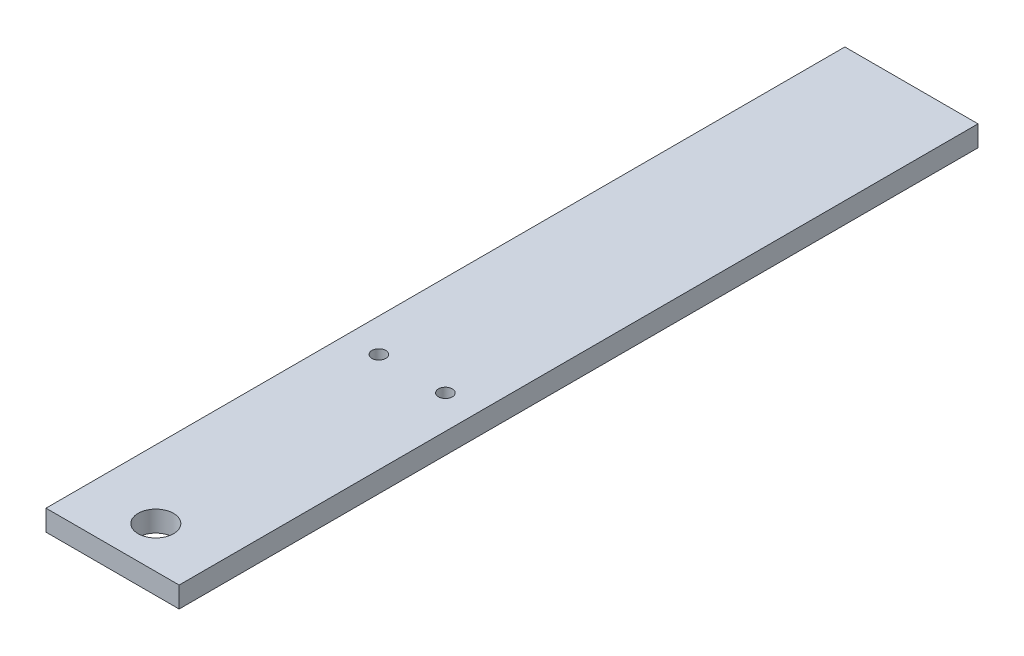
SolidWorks part; units mm, degrees
ref_plane "Front Plane" through (0, 0, 0) normal (0, 0, 1) x (1, 0, 0)
ref_plane "Top Plane" through (0, 0, 0) normal (0, 1, 0) x (1, 0, 0)
ref_plane "Right Plane" through (0, 0, 0) normal (1, 0, 0) x (0, 0, -1)
sketch "Sketch1" plane through (0, 0, 0) normal (0, 0, 1) x (1, 0, 0)
  line L0 (0, 3.9688) -> (0, -3.9688)
  line L1 (-25.4, 0) -> (25.4, 0) construction
  point P6 (0, 0)
  dimension "Width" = 50.8
  dimension "Thk" = 7.9375
sketch "Sketch2" plane through (0, 0, 0) normal (1, 0, 0) x (0, 0, -1)
  line L0 (76.2, 0) -> (-76.2, 0)
  point P4 (0, 0)
  dimension "Length" = 152.4
sketch "Sketch3" plane through (0, 0, 0) normal (0, 0, 1) x (1, 0, 0)
  line L1 (25.4, 3.9688) -> (-25.4, 3.9688)
  line L2 (25.4, 3.9688) -> (25.4, -3.9688)
  line L3 (25.4, -3.9688) -> (-25.4, -3.9688)
  line L4 (-25.4, 3.9688) -> (-25.4, -3.9688)
  line L5 (25.4, 3.9688) -> (-25.4, -3.9688) construction
  line L6 (25.4, -3.9688) -> (-25.4, 3.9688) construction
  point P0 (0, 0)
extrude "Boss-Extrude1" add sketch "Sketch3" along normal up to vertex (76.2 mm away) and the other way up to vertex (76.2 mm away) up to point (0, 0, 76.2) other way up to point (0, 0, -76.2)
sketch "Sketch4" plane through (0, 3.9688, 0) normal (0, 1, 0) x (1, 0, 0)
  point P0 (0.6258, -60.325)
hole_wizard "M12 Clearance Hole2" positions "Sketch5" profile "Sketch7" hole size "M12" standard "ANSI Metric" end condition through all
sketch "Sketch5" plane through (0, 3.9688, 0) normal (0, 1, 0) x (1, 0, 0)
  point P0 (0.6258, -60.325)
sketch "Sketch7" plane through (0.6258, 3.9688, 60.325) normal (1, 0, 0) x (0, 0, 1)
  line L0 (0, 0) -> (0, 7.9375)
  line L1 (0, 7.9375) -> (6.75, 7.9375)
  line L2 (6.75, 7.9375) -> (6.75, 0)
  line L5 (6.75, 0) -> (0, 0)
  line L11 (0, -6.35) -> (0, 107.95) construction
  dimension "Thru Hole Dia." = 13.5
  dimension "Thru Hole Depth" = 7.9375
sketch "Sketch8" plane through (0, 3.9688, 0) normal (0, 1, 0) x (1, 0, 0)
  point P1 (0.6258, -38.1)
hole_wizard "M12 Clearance Hole1" [suppressed] positions "Sketch9" profile "Sketch10" hole size "M12" standard "ANSI Metric"
sketch "Sketch9" plane through (0, 3.9688, 0) normal (0, 1, 0) x (1, 0, 0)
  point P5 (0.6258, -38.1)
sketch "Sketch10" plane through (0.6258, 3.9688, 38.1) normal (1, 0, 0) x (0, 0, 1)
  line L0 (0, 0) -> (0, 7.9375)
  line L1 (0, 7.9375) -> (6.75, 7.9375)
  line L2 (6.75, 7.9375) -> (6.75, 0)
  line L5 (6.75, 0) -> (0, 0)
  line L11 (0, -6.35) -> (0, 107.95) construction
  dimension "Thru Hole Dia." = 13.5
  dimension "Thru Hole Depth" = 7.9375
sketch "Sketch11" plane through (0, 3.9688, 0) normal (0, 1, 0) x (1, 0, 0)
  circle A0 centre (0.6258, -38.1) radius 7.25
  dimension "D1" = 14.5
extrude "Cut-Extrude1" [suppressed] cut sketch "Sketch11" against normal blind 4.5 contours A0
sketch "Sketch12" plane through (0, -3.9688, 0) normal (0, 1, 0) x (1, 0, 0)
  line L0 (-12.7, 38.1) -> (12.7, 38.1) construction
  line L1 (25.4, 76.2) -> (-25.4, 76.2) construction
  point P2 (0, 38.1)
  point P5 (0, 76.2)
  point P7 (12.7, 38.1)
  point P8 (-12.7, 38.1)
  dimension "D1" = 25.4
  dimension "D2" = 38.1
hole_wizard "CSK for M5 Flat Head Machine Screw1" positions "Sketch15" profile "Sketch17" countersink size "M5" standard "ANSI Metric" end condition up to next
sketch "Sketch15" plane through (0, -3.9688, 0) normal (0, -1, 0) x (-1, 0, 0)
  point P0 (-12.7, 38.1)
  point P3 (12.7, 38.1)
sketch "Sketch17" plane through (12.7, -3.9688, -38.1) normal (1, 0, 0) x (0, 0, -1)
  line L0 (0, 0) -> (0, 7.9375)
  line L1 (0, 7.9375) -> (2.65, 7.9375)
  line L2 (2.65, 7.9375) -> (2.65, 2.55)
  line L3 (2.65, 2.55) -> (5.2, 0)
  line L5 (5.2, 0) -> (0, 0)
  line L6 (-2.65, 2.55) -> (-5.2, 0) construction
  line L11 (0, -6.35) -> (0, 107.95) construction
  dimension "Thru Hole Dia." = 5.3
  dimension "Thru Hole Depth" = 7.9375
  dimension "Near C'Sink Dia." = 10.4
  dimension "Near C'Sink Angle" = 90
ref_plane "Plane1" through (25.4, 3.9688, -76.2) normal (-1, 0, 0) x (0, 0, 1)
sketch "Sketch19" plane through (0, 3.9688, 0) normal (0, 1, 0) x (1, 0, 0)
  line L0 (12.7, 60.325) -> (-12.7, 60.325) construction
  line L1 (25.4, 76.2) -> (-25.4, 76.2) construction
  point P4 (0, 60.325)
  point P5 (0, 76.2)
  point P7 (-12.7, 60.325)
  point P8 (12.7, 60.325)
  dimension "D1" = 15.875
  dimension "D2" = 25.4
hole_wizard "CSK for M5 Flat Head Machine Screw2" [suppressed] positions "Sketch20" profile "Sketch21" countersink size "M5" standard "ANSI Metric"
sketch "Sketch20" plane through (0, 3.9688, 0) normal (0, 1, 0) x (1, 0, 0)
  point P0 (12.7, 60.325)
  point P3 (-12.7, 60.325)
sketch "Sketch21" plane through (12.7, 3.9688, -60.325) normal (1, 0, 0) x (0, 0, 1)
  line L0 (0, 0) -> (0, 7.9375)
  line L1 (0, 7.9375) -> (2.65, 7.9375)
  line L2 (2.65, 7.9375) -> (2.65, 2.55)
  line L3 (2.65, 2.55) -> (5.2, 0)
  line L5 (5.2, 0) -> (0, 0)
  line L6 (-2.65, 2.55) -> (-5.2, 0) construction
  line L11 (0, -6.35) -> (0, 107.95) construction
  dimension "Thru Hole Dia." = 5.3
  dimension "Thru Hole Depth" = 7.9375
  dimension "Near C'Sink Dia." = 10.4
  dimension "Near C'Sink Angle" = 90
sketch "Sketch22" [suppressed] plane through (0, 3.9688, 0) normal (0, 1, 0) x (1, 0, 0)
  point P0 (-12.7, -73.025)
  point P1 (12.7, -73.025)
  point P2 (12.7, -3.175)
  point P4 (-12.7, -3.175)
hole_wizard "CSK for M3 Flat Head Machine Screw1" [suppressed] positions "Sketch23" profile "Sketch25" countersink size "M3" standard "ANSI Metric"
sketch "Sketch23" [suppressed] plane through (0, 3.9688, 0) normal (0, 1, 0) x (1, 0, 0)
  point P0 (-12.7, -73.025)
  point P3 (12.7, -73.025)
  point P6 (12.7, -3.175)
  point P9 (-12.7, -3.175)
sketch "Sketch25" plane through (-12.7, 3.9688, 73.025) normal (1, 0, 0) x (0, 0, 1)
  line L0 (0, 0) -> (0, 7.9375)
  line L1 (0, 7.9375) -> (1.7, 7.9375)
  line L2 (1.7, 7.9375) -> (1.7, 1.45)
  line L3 (1.7, 1.45) -> (3.15, 0)
  line L5 (3.15, 0) -> (0, 0)
  line L6 (-1.7, 1.45) -> (-3.15, 0) construction
  line L11 (0, -6.35) -> (0, 107.95) construction
  dimension "Thru Hole Dia." = 3.4
  dimension "Thru Hole Depth" = 7.9375
  dimension "Near C'Sink Dia." = 6.3
  dimension "Near C'Sink Angle" = 90
sketch "Sketch26" plane through (0, 3.9688, 0) normal (0, 1, 0) x (1, 0, 0)
  line L0 (-25.4, -76.2) -> (-25.4, 76.2) construction
  line L1 (25.4, 76.2) -> (-25.4, 76.2)
  line L2 (25.4, 76.2) -> (25.4, 228.6)
  line L3 (25.4, 228.6) -> (-25.4, 228.6)
  line L4 (-25.4, 76.2) -> (-25.4, 228.6)
  dimension "D1" = 152.4
extrude "Boss-Extrude2" add sketch "Sketch26" against normal up to surface (7.9375 mm away) up to face at (-12.7, -3.9688, -43.3)
